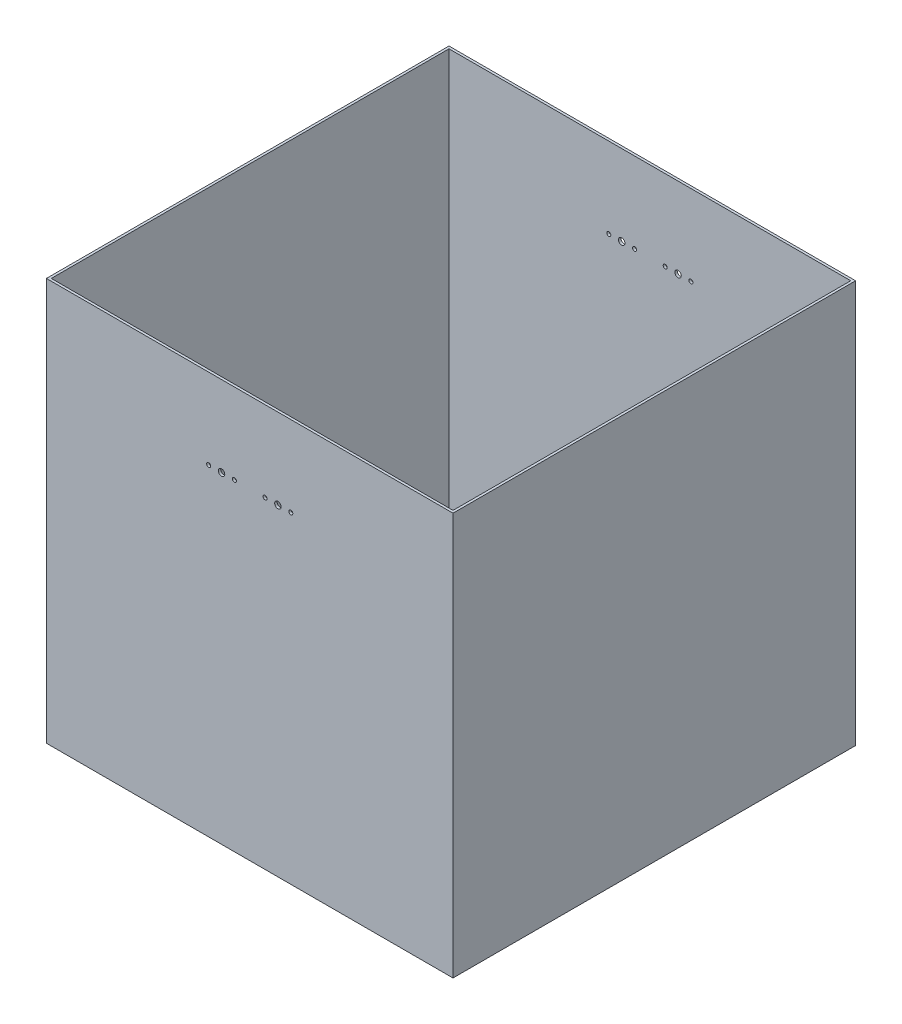
SolidWorks part; units mm, degrees
material "Acrylic (Medium-high impact)"
ref_plane "Front Plane" through (0, 0, 0) normal (0, 0, 1) x (1, 0, 0)
ref_plane "Top Plane" through (0, 0, 0) normal (0, 1, 0) x (1, 0, 0)
ref_plane "Right Plane" through (0, 0, 0) normal (1, 0, 0) x (0, 0, -1)
sketch "Sketch1" plane through (0, 0, 0) normal (0, 1, 0) x (1, 0, 0)
  line L0 (-249.5, 247) -> (249.5, 247)
  line L1 (-252.5, 250) -> (252.5, 250)
  line L2 (-252.5, 250) -> (-252.5, -250)
  line L3 (-252.5, -250) -> (252.5, -250)
  line L4 (252.5, 250) -> (252.5, -250)
  line L5 (-252.5, 250) -> (252.5, -250) construction
  line L6 (-252.5, -250) -> (252.5, 250) construction
  line L7 (249.5, 247) -> (249.5, -247)
  line L8 (-249.5, -247) -> (249.5, -247)
  line L9 (-249.5, 247) -> (-249.5, -247)
  circle A0 centre (0, 0) radius 252.5 construction
  point P0 (0, 0)
  dimension "D1" = 505
  dimension "D2" = 500
  dimension "D3" = 3
extrude "Boss-Extrude1" add sketch "Sketch1" along normal blind 500
sketch "Sketch2" plane through (0, 500, 0) normal (0, 1, 0) x (1, 0, 0)
  line L0 (-254.6839, 0.2203) -> (252.5, 0.2203) construction
  line L1 (-254.6839, -249.5595) -> (252.5, -249.5595) construction
  line L2 (-254.6839, -249.5595) -> (-254.6839, 250) construction
  line L3 (-254.6839, 250) -> (252.5, 250) construction
  line L4 (252.5, -249.5595) -> (252.5, 250) construction
  line L5 (-254.6839, -249.5595) -> (252.5, 250) construction
  line L6 (-254.6839, 250) -> (252.5, -249.5595) construction
  point P0 (-1.0919, 0.2203)
sketch "Sketch4" plane through (0, 0, -250) normal (0, 0, -1) x (-1, 0, 0)
  line L0 (-35, 400) -> (35, 400) construction
  line L1 (0, 0) -> (0, 400) construction
  line L2 (-252.5, 0) -> (252.5, 0) construction
  line L3 (-35, 400) -> (-35, 391.4181) construction
  circle A0 centre (35, 400) radius 4
  circle A1 centre (-35, 400) radius 4
  circle A2 centre (-19, 400) radius 2.5
  circle A3 centre (-51, 400) radius 2.5
  circle A4 centre (19, 400) radius 2.5
  circle A5 centre (51, 400) radius 2.5
  point P6 (0, 400)
  dimension "D2" = 8
  dimension "D3" = 5
  dimension "D1" = 35
  dimension "D4" = 16
  dimension "D5" = 400
extrude "Cut-Extrude2" cut sketch "Sketch4" against normal through all both
